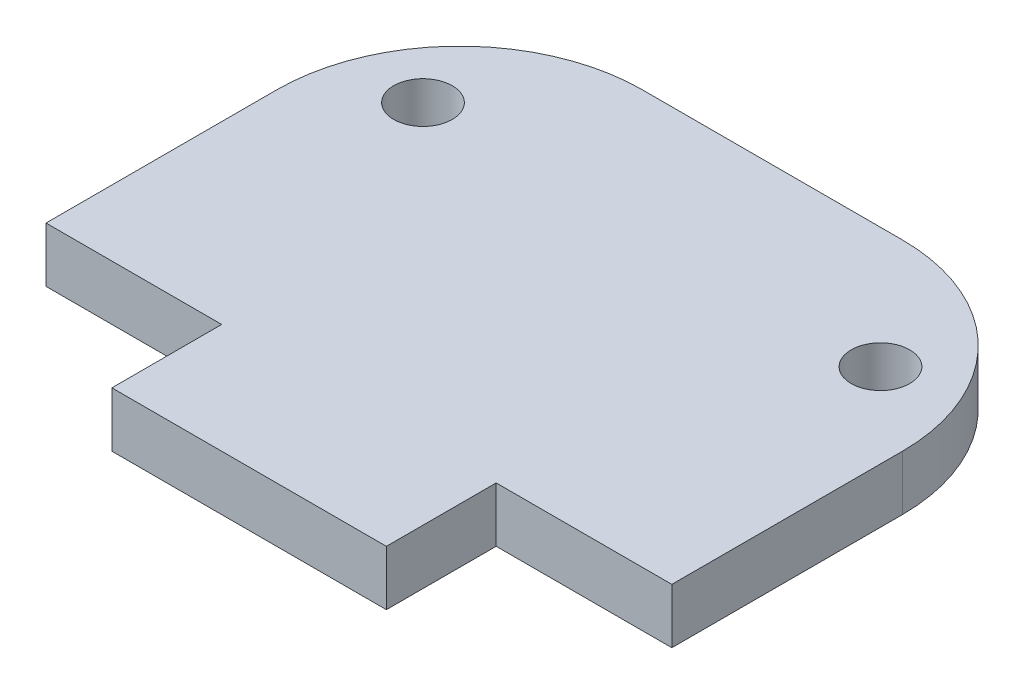
SolidWorks part; units mm, degrees
ref_plane "Plano frontal" through (0, 0, 0) normal (0, 0, 1) x (1, 0, 0)
ref_plane "Plano superior" through (0, 0, 0) normal (0, 1, 0) x (1, 0, 0)
ref_plane "Plano direito" through (0, 0, 0) normal (1, 0, 0) x (0, 0, -1)
ref_plane "Plano1" through (0, -3, 0) normal (0, -1, 0) x (1, 0, 0)
sketch "Esboço1" plane through (0, -3, 0) normal (0, -1, 0) x (1, 0, 0)
  line L0 (-7.1, -28.6) -> (7.1, -28.6)
  line L1 (17.1, -18.6) -> (17.1, -6)
  line L2 (17.1, -6) -> (7.5, -6)
  line L3 (7.5, -6) -> (7.5, 0)
  line L4 (7.5, 0) -> (-7.5, 0)
  line L5 (-7.5, 0) -> (-7.5, -6)
  line L6 (-7.5, -6) -> (-17.1, -6)
  line L7 (-17.1, -6) -> (-17.1, -18.6)
  line L8 (-12.5, -22) -> (12.5, -22) construction
  line L9 (-7.5, -6) -> (7.5, -6) construction
  arc A0 (7.1, -28.6) -> (17.1, -18.6) centre (7.1, -18.6) ccw
  arc A1 (-17.1, -18.6) -> (-7.1, -28.6) centre (-7.1, -18.6) ccw
  circle A2 centre (-12.5, -22) radius 1.6
  circle A3 centre (12.5, -22) radius 1.6
  point P16 (0, 0)
  point P17 (0, -22)
  point P18 (0, -6)
  point P19 (16.5026, -8.1549)
  dimension "D1" = 25
  dimension "D2" = 3.2
  dimension "D6" = 10
  dimension "D3" = 15
  dimension "D4" = 6
  dimension "D5" = 22.6
  dimension "D7" = 6.6
  dimension "D8" = 4.6
extrude "Ressalto-extrusão1" add sketch "Esboço1" against normal blind 3
